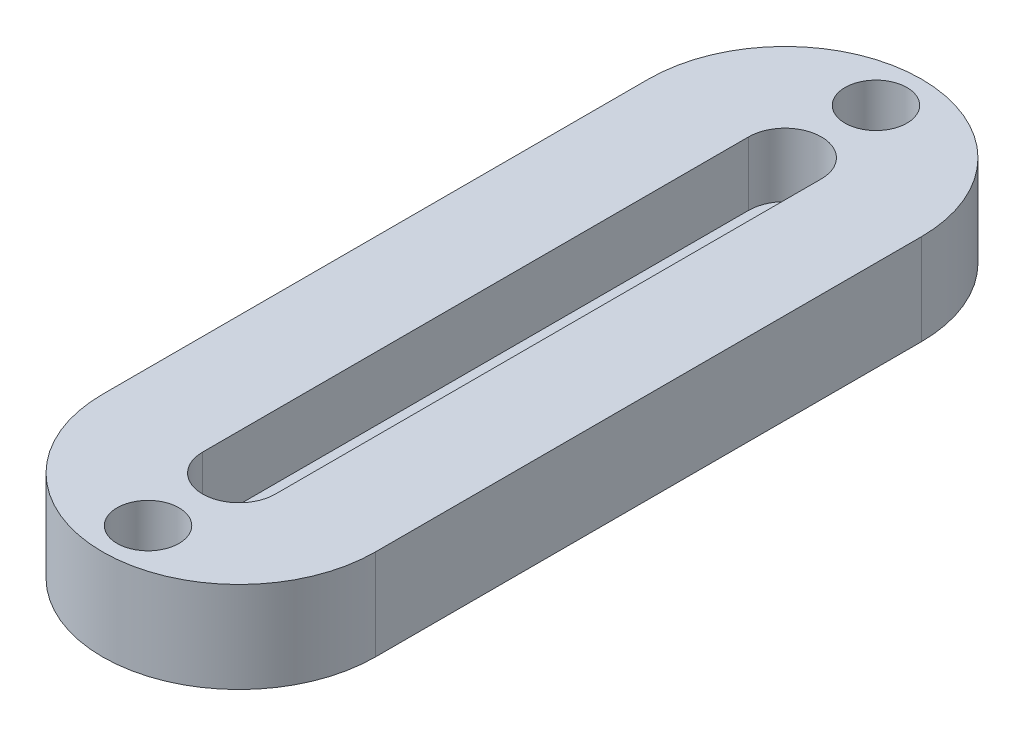
SolidWorks part; units mm, degrees
ref_plane "Front Plane" through (0, 0, 0) normal (0, 0, 1) x (1, 0, 0)
ref_plane "Top Plane" through (0, 0, 0) normal (0, 1, 0) x (1, 0, 0)
ref_plane "Right Plane" through (0, 0, 0) normal (1, 0, 0) x (0, 0, -1)
sketch "Sketch1" plane through (0, 0, 0) normal (0, 1, 0) x (1, 0, 0)
  line L0 (0, 0) -> (0, 38.1)
  line L1 (5.08, 38.1) -> (5.08, 0)
  line L2 (-6.985, 38.1) -> (-6.985, 0)
  line L3 (12.065, 38.1) -> (12.065, 0)
  arc A0 (0, 38.1) -> (5.08, 38.1) centre (2.54, 38.1) cw
  arc A1 (0, 0) -> (5.08, 0) centre (2.54, 0) ccw
  arc A2 (-6.985, 38.1) -> (12.065, 38.1) centre (2.54, 38.1) cw
  arc A3 (-6.985, 0) -> (12.065, 0) centre (2.54, 0) ccw
  point P10 (1.651, 38.1507)
  point P11 (1.651, 38.1507)
  point P12 (1.651, 38.1507)
  point P13 (1.651, 38.1507)
  dimension "D1" = 5.08
  dimension "D2" = 38.1
  dimension "D3" = 0
  dimension "D4" = 19.05
extrude "Boss-Extrude1" add sketch "Sketch1" along normal blind 6.35
ref_plane "Plane1" through (0, 6.35, -38.1) normal (0, 0, 1) x (1, 0, 0)
sketch "Sketch2" plane through (0, 0, 0) normal (0, 1, 0) x (1, 0, 0)
  line L0 (-10.4775, 38.1) -> (10.4775, 38.1) construction
  line L1 (0, 38.1) -> (0, 0)
  line L2 (5.08, 38.1) -> (5.08, 0)
  arc A0 (0, 38.1) -> (5.08, 38.1) centre (2.54, 38.1) cw
  arc A1 (5.08, 38.1) -> (0, 38.1) centre (2.54, 38.1) ccw construction
  arc A2 (0, 0) -> (5.08, 0) centre (2.54, 0) ccw
extrude "Boss-Extrude2" add sketch "Sketch2" along normal blind 1.905
sketch "Sketch3" plane through (0, 6.35, 0) normal (0, 1, 0) x (1, 0, 0)
  circle A0 centre (2.54, 44.45) radius 2.159
  circle A1 centre (2.54, -6.35) radius 2.159
  arc A2 (0, 0) -> (5.08, 0) centre (2.54, 0) ccw construction
  point P4 (2.54, 0)
  point P7 (2.54, 38.1)
  dimension "D1" = 0
  dimension "D4" = 6.35
  dimension "D2" = 6.35
  dimension "D3" = 0
extrude "Cut-Extrude1" cut sketch "Sketch3" against normal blind 12.7
